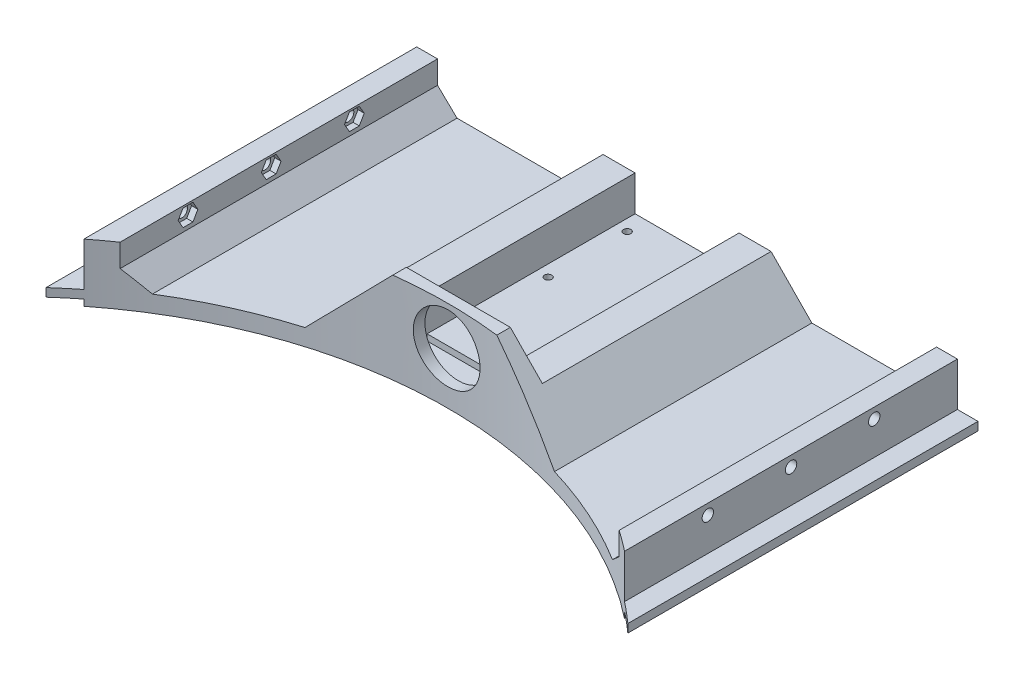
SolidWorks part; units mm, degrees
ref_plane "Front Plane" through (0, 0, 0) normal (0, 0, 1) x (1, 0, 0)
ref_plane "Top Plane" through (0, 0, 0) normal (0, 1, 0) x (1, 0, 0)
ref_plane "Right Plane" through (0, 0, 0) normal (1, 0, 0) x (0, 0, -1)
sketch "Sketch1" plane through (0, 0, 0) normal (0, 1, 0) x (1, 0, 0)
  line L0 (0, 0) -> (0, 650)
  line L1 (0, 650) -> (650, 650)
  line L2 (650, 650) -> (650, 0)
  line L3 (650, 0) -> (0, 0)
  dimension "D1" = 650
  dimension "D2" = 650
extrude "Boss-Extrude1" add sketch "Sketch1" along normal blind 8
sketch "Sketch3" plane through (0, 0, 0) normal (0, 0, 1) x (1, 0, 0)
  line L0 (325, 8) -> (325, 43.7071) construction
  line L1 (0, 8) -> (650, 8) construction
  line L2 (300, 43.7071) -> (350, 43.7071)
  line L3 (300, 43.7071) -> (265, 8)
  line L4 (265, 8) -> (385, 8)
  line L5 (385, 8) -> (350, 43.7071)
  point P7 (325, 43.7071)
  dimension "D1" = 50
  dimension "D2" = 50
  dimension "D3" = 50
  dimension "D4" = 120
extrude "Boss-Extrude2" add sketch "Sketch3" against normal blind 650
sketch "Sketch4" plane through (0, 0, 0) normal (0, 0, 1) x (1, 0, 0)
  line L0 (265, 8) -> (385, 8) construction
  circle A0 centre (325, 25) radius 16.05
  dimension "D1" = 17
  dimension "D2" = 32.1
extrude "Cut-Extrude2" cut sketch "Sketch4" against normal through all both and the other way through all
sketch "Sketch2" plane through (0, 8, 0) normal (0, 1, 0) x (1, 0, 0)
  line L0 (0, 650) -> (0, 0) construction
  line L1 (650, 650) -> (385, 650) construction
  circle A0 centre (325, 325) radius 210
  dimension "D3" = 420
  dimension "D1" = 325
  dimension "D2" = 325
extrude "Cut-Extrude1" cut sketch "Sketch2" against normal through all both and the other way through all
sketch "Sketch5" plane through (0, 0, 0) normal (0, 0, 1) x (1, 0, 0)
  line L0 (300, 43.7071) -> (350, 43.7071)
  line L1 (265, 8) -> (385, 8) construction
  line L2 (300, 8) -> (300, 28)
  line L3 (300, 8) -> (350, 8)
  line L4 (350, 8) -> (350, 28)
  line L5 (350, 28) -> (365.3961, 28)
  line L6 (385, 8) -> (350, 43.7071) construction
  line L7 (365.3961, 28) -> (350, 43.7071)
  line L8 (300, 28) -> (284.6039, 28)
  line L9 (300, 43.7071) -> (265, 8) construction
  line L10 (284.6039, 28) -> (300, 43.7071)
extrude "Cut-Extrude3" cut sketch "Sketch5" against normal blind 110 and the other way through all
sketch "Sketch6" plane through (0, 0, -650) normal (0, 0, -1) x (-1, 0, 0)
  line L0 (-265, 8) -> (-385, 8) construction
  line L1 (-350, 43.7071) -> (-300, 43.7071)
  line L2 (-300, 8) -> (-300, 28)
  line L3 (-300, 28) -> (-284.6039, 28)
  line L4 (-300, 43.7071) -> (-265, 8) construction
  line L5 (-284.6039, 28) -> (-300, 43.7071)
  line L6 (-350, 8) -> (-350, 28)
  line L7 (-350, 28) -> (-365.3961, 28)
  line L8 (-365.3961, 28) -> (-350, 43.7071)
  line L9 (-350, 8) -> (-300, 8)
extrude "Cut-Extrude4" cut sketch "Sketch6" against normal blind 110
sketch "Sketch7" plane through (0, 8, 0) normal (0, 1, 0) x (1, 0, 0)
  line L1 (325, 325) -> (325, 455) construction
  line L2 (325, 325) -> (325, 195) construction
  line L3 (325, 325) -> (455, 325) construction
  line L4 (325, 325) -> (195, 325) construction
  line L9 (325, 455) -> (455, 455) construction
  line L10 (455, 455) -> (455, 195) construction
  line L11 (455, 195) -> (195, 195) construction
  line L12 (195, 195) -> (195, 455) construction
  line L13 (195, 455) -> (325, 455) construction
  line L14 (195, 455) -> (195, 686.5445)
  line L15 (195, 686.5445) -> (455, 686.5445)
  line L16 (455, 686.5445) -> (455, 455)
  line L17 (455, 455) -> (195, 455)
  dimension "D1" = 130
  dimension "D2" = 130
  dimension "D3" = 130
  dimension "D4" = 130
extrude "Cut-Extrude5" cut sketch "Sketch7" against normal through all both and the other way through all flip side to cut
sketch "Sketch8" plane through (0, 0, -650) normal (0, 0, -1) x (-1, 0, 0)
  line L0 (-455, 8) -> (-455, 28)
  line L1 (-455, 28) -> (-445, 28)
  line L2 (-445, 28) -> (-445, 17)
  line L3 (-445, 17) -> (-435.6192, 8)
  line L4 (-455, 8) -> (-385, 8) construction
  line L5 (-435.6192, 8) -> (-455, 8)
  line L6 (-195, 8) -> (-195, 28)
  line L7 (-195, 28) -> (-205, 28)
  line L8 (-205, 28) -> (-205, 17)
  line L9 (-205, 17) -> (-214.3808, 8)
  line L10 (-265, 8) -> (-195, 8) construction
  line L11 (-214.3808, 8) -> (-195, 8)
  dimension "D1" = 20
  dimension "D2" = 10
  dimension "D3" = 13
  dimension "D4" = 20
  dimension "D5" = 10
  dimension "D6" = 13
  dimension "D7" = 11
  dimension "D8" = 11
extrude "Boss-Extrude3" add sketch "Sketch8" against normal blind 170
sketch "Sketch9" plane through (0, 0, -650) normal (0, 0, -1) x (-1, 0, 0)
  line L0 (-455, 7) -> (-464.9, 7)
  line L1 (-455, 0) -> (-455, 28) construction
  line L2 (-464.9, 7) -> (-464.9, 3)
  line L3 (-464.9, 3) -> (-455, 3)
  line L4 (-455, 3) -> (-455, 7)
  line L5 (-455, 0) -> (-195, 0) construction
  line L6 (-195, 3) -> (-195, 7)
  line L7 (-195, 28) -> (-195, 0) construction
  line L8 (-195, 7) -> (-185.1, 7)
  line L9 (-185.1, 7) -> (-185.1, 3)
  line L10 (-185.1, 3) -> (-195, 3)
  dimension "D1" = 3
  dimension "D2" = 4
  dimension "D3" = 3
  dimension "D4" = 4
  dimension "D5" = 9.9
  dimension "D6" = 9.9
extrude "Boss-Extrude4" add sketch "Sketch9" against normal blind 170
sketch "Sketch10" plane through (0, 8, 0) normal (0, 1, 0) x (1, 0, 0)
  line L0 (0, 0) -> (0, 650) construction
  line L1 (0, 650) -> (650, 650) construction
  line L2 (650, 650) -> (0, 0) construction
  circle A0 centre (325, 325) radius 210
extrude "Cut-Extrude6" cut sketch "Sketch10" against normal through all both and the other way through all
sketch "Sketch11" plane through (0, 0, -650) normal (0, 0, -1) x (-1, 0, 0)
  line L0 (-350, 8) -> (-350, 11)
  line L1 (-350, 28) -> (-350, 8) construction
  line L2 (-350, 11) -> (-300, 11)
  line L3 (-300, 8) -> (-300, 28) construction
  line L4 (-300, 11) -> (-300, 8)
  line L5 (-300, 8) -> (-350, 8)
  dimension "D1" = 3
extrude "Boss-Extrude5" add sketch "Sketch11" against normal blind 100
sketch "Sketch12" plane through (0, 11, 0) normal (0, 1, 0) x (1, 0, 0)
  line L0 (300, 650) -> (350, 650) construction
  line L1 (300, 550) -> (300, 650) construction
  line L2 (300, 540) -> (300, 650) construction
  line L3 (350, 540) -> (350, 650) construction
  circle A0 centre (305.5, 640.7) radius 1.75
  circle A1 centre (344.5, 640.7) radius 1.75
  circle A2 centre (344.5, 602.7) radius 1.75
  circle A3 centre (305.5, 602.7) radius 1.75
  dimension "D9" = 3.5
  dimension "D10" = 3.5
  dimension "D11" = 3.5
  dimension "D12" = 3.5
  dimension "D1" = 9.3
  dimension "D2" = 9.3
  dimension "D3" = 5.5
  dimension "D4" = 5.5
  dimension "D5" = 5.5
  dimension "D6" = 5.5
  dimension "D7" = 38
  dimension "D8" = 38
extrude "Cut-Extrude7" cut sketch "Sketch12" against normal through all both and the other way through all
sketch "Sketch13" plane through (455, 0, 0) normal (1, 0, 0) x (0, 0, -1)
  line L1 (650, 7) -> (650, 28) construction
  line L2 (489.9242, 28) -> (650, 28) construction
  circle A0 centre (610, 23) radius 2.75
  circle A1 centre (570, 23) radius 2.75
  circle A2 centre (530, 23) radius 2.75
  dimension "D4" = 5.5
  dimension "D5" = 5.5
  dimension "D6" = 5.5
  dimension "D1" = 40
  dimension "D2" = 40
  dimension "D3" = 40
  dimension "D7" = 5
  dimension "D8" = 5
  dimension "D9" = 5
extrude "Cut-Extrude8" cut sketch "Sketch13" against normal blind 10 and the other way through all
sketch "Sketch14" plane through (195, 0, 0) normal (-1, 0, 0) x (0, 0, 1)
  line L0 (-650, 28) -> (-650, 7) construction
  line L1 (-489.9242, 28) -> (-650, 28) construction
  circle A0 centre (-610, 23) radius 2.75
  circle A1 centre (-570, 23) radius 2.75
  circle A2 centre (-530, 23) radius 2.75
  dimension "D1" = 5.5
  dimension "D2" = 5.5
  dimension "D3" = 5.5
  dimension "D4" = 40
  dimension "D5" = 40
  dimension "D6" = 40
  dimension "D7" = 5
  dimension "D8" = 5
  dimension "D9" = 5
extrude "Cut-Extrude9" cut sketch "Sketch14" against normal blind 10
sketch "Sketch15" plane through (205, 0, 0) normal (1, 0, 0) x (0, 0, -1)
  line L0 (530, 23) -> (530, 27.1) construction
  line L1 (530, 23) -> (530, 18.9) construction
  line L2 (530, 27.1) -> (527.63, 27.1)
  line L3 (530, 27.1) -> (532.37, 27.1)
  line L4 (532.37, 27.1) -> (534.7371, 23)
  line L5 (534.7371, 23) -> (532.37, 18.9)
  line L6 (532.37, 18.9) -> (530, 18.9)
  line L7 (530, 18.9) -> (527.63, 18.9)
  line L8 (527.63, 18.9) -> (525.2629, 23)
  line L9 (525.2629, 23) -> (527.63, 27.1)
  dimension "D1" = 4.1
  dimension "D2" = 4.1
  dimension "D3" = 120
  dimension "D4" = 2.37
extrude "Cut-Extrude10" cut sketch "Sketch15" against normal blind 3
pattern_linear "LPattern1" count 3 spacing 40 along (0, 0, -1) of "Cut-Extrude10"
sketch "Sketch16" plane through (445, 0, 0) normal (-1, 0, 0) x (0, 0, 1)
  line L0 (-610, 23) -> (-610, 27.1) construction
  line L1 (-610, 23) -> (-610, 18.9) construction
  line L2 (-610, 27.1) -> (-607.63, 27.1)
  line L3 (-610, 27.1) -> (-612.37, 27.1)
  line L4 (-612.37, 27.1) -> (-614.7371, 23)
  line L5 (-614.7371, 23) -> (-612.37, 18.9)
  line L6 (-612.37, 18.9) -> (-610, 18.9)
  line L7 (-607.63, 18.9) -> (-610, 18.9)
  line L8 (-607.63, 18.9) -> (-605.2629, 23)
  line L9 (-605.2629, 23) -> (-607.63, 27.1)
  dimension "D1" = 4.1
  dimension "D2" = 4.1
  dimension "D3" = 120
  dimension "D4" = 2.37
extrude "Cut-Extrude11" cut sketch "Sketch16" against normal blind 3
pattern_linear "LPattern2" count 3 spacing 40 along (0, 0, 1) of "Cut-Extrude11"
sketch "Sketch17" plane through (0, 0, 0) normal (0, -1, 0) x (-1, 0, 0)
  line L0 (-332.6, 539.9) -> (-317.5, 539.9)
  line L1 (-317.5, 539.9) -> (-317.5, 640)
  line L2 (-317.5, 640) -> (-332.6, 640)
  line L3 (-332.6, 640) -> (-332.6, 539.9)
  line L4 (-455, 650) -> (-195, 650) construction
  line L5 (-195, 489.9242) -> (-195, 650) construction
  point P6 (-325, 650)
  dimension "D1" = 15.1
  dimension "D2" = 100.1
  dimension "D3" = 10
  dimension "D4" = 122.5
extrude "Cut-Extrude12" cut sketch "Sketch17" against normal blind 3
